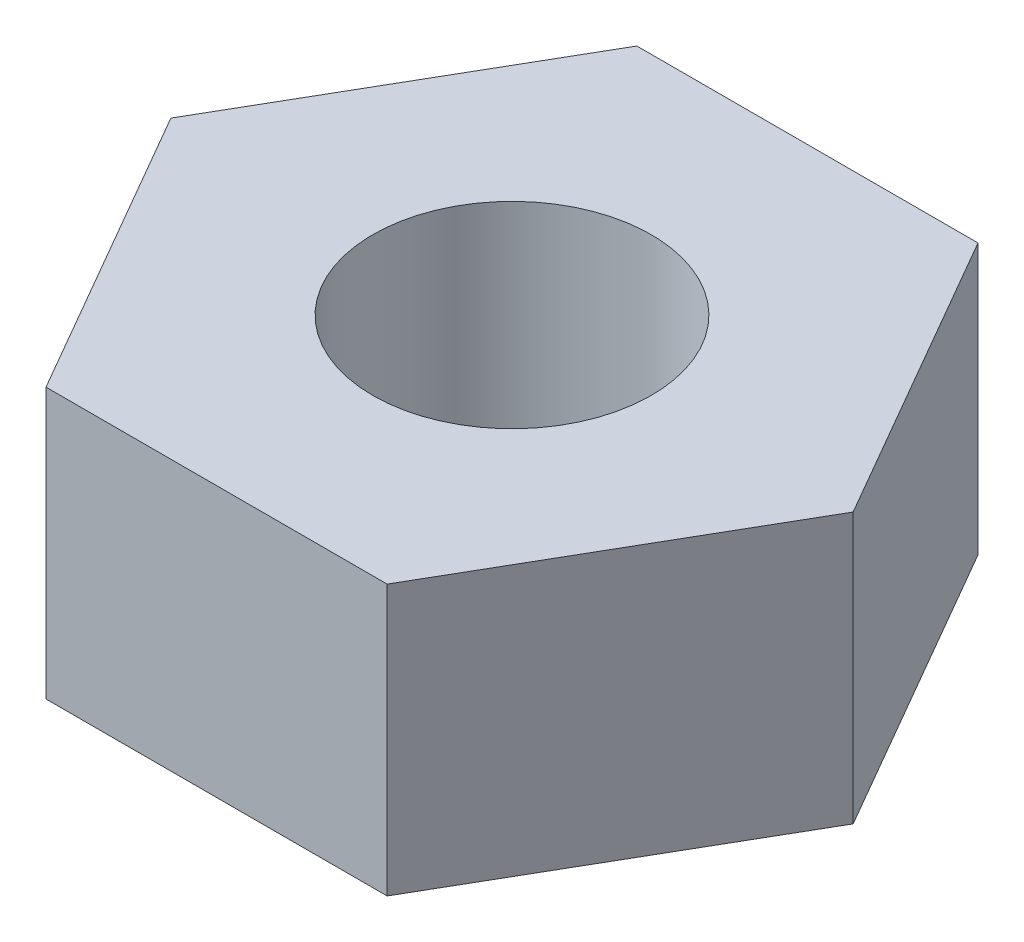
SolidWorks part; units mm, degrees
material "acero"
ref_plane "Alzado" through (0, 0, 0) normal (0, 0, 1) x (1, 0, 0)
ref_plane "Planta" through (0, 0, 0) normal (0, 1, 0) x (1, 0, 0)
ref_plane "Vista lateral" through (0, 0, 0) normal (1, 0, 0) x (0, 0, -1)
sketch "Croquis1" plane through (0, 0, 0) normal (0, 1, 0) x (1, 0, 0)
  line L1 (-2.0207, 3.5) -> (-4.0415, 0)
  line L2 (-4.0415, 0) -> (-2.0207, -3.5)
  line L3 (-2.0207, -3.5) -> (2.0207, -3.5)
  line L4 (2.0207, -3.5) -> (4.0415, 0)
  line L5 (4.0415, 0) -> (2.0207, 3.5)
  line L6 (2.0207, 3.5) -> (-2.0207, 3.5)
  circle A0 centre (0, 0) radius 3.5 construction
  circle A1 centre (0, 0) radius 1.65
  dimension "D1" = 7
  dimension "D2" = 3.3
extrude "Saliente-Extruir1" add sketch "Croquis1" along normal blind 3.2
